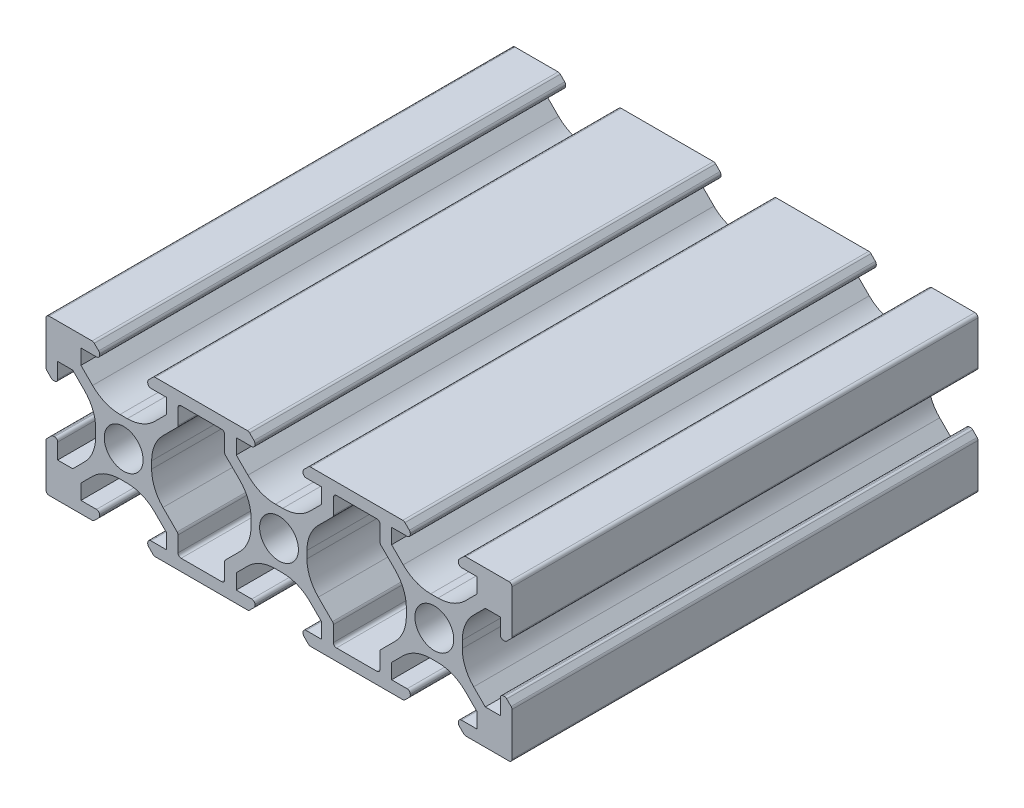
SolidWorks part; units mm, degrees
material "6063-O"
ref_plane "Plano frontal" through (0, 0, 0) normal (0, 0, 1) x (1, 0, 0)
ref_plane "Plano superior" through (0, 0, 0) normal (0, 1, 0) x (1, 0, 0)
ref_plane "Plano direito" through (0, 0, 0) normal (1, 0, 0) x (0, 0, -1)
sketch "Esboço1" plane through (0, 0, 0) normal (0, 0, 1) x (1, 0, 0)
  line L0 (-9.0343, 3.1) -> (-8.9, 3.1)
  line L3 (-10, 10) -> (-4.0657, 10)
  line L5 (-10, -10) -> (10, 10) construction
  line L6 (-10, 10) -> (10, -10) construction
  line L7 (-8.5, 3.5) -> (-8.5, 5.5)
  line L8 (-10, 0) -> (10, 0) construction
  line L9 (0, 10) -> (0, -10) construction
  line L12 (-8.5, 5.5) -> (-6.5607, 5.5)
  line L15 (-6.5607, 5.5) -> (-5.0645, 4.0038)
  line L16 (-3.6, 0.4683) -> (-3.6, 0)
  line L17 (-0.4683, 3.6) -> (0, 3.6)
  line L18 (-5.5, 6.5607) -> (-4.0038, 5.0645)
  line L21 (-5.5, 8.5) -> (-5.5, 6.5607)
  line L24 (-3.5, 8.5) -> (-5.5, 8.5)
  line L25 (-3.1, 9.0343) -> (-3.1, 8.9)
  line L44 (-10, 4.0657) -> (-10, 10)
  line L45 (-9.8828, 3.7828) -> (-9.3172, 3.2172)
  line L46 (-3.7828, 9.8828) -> (-3.2172, 9.3172)
  line L47 (-3.6, 0) -> (-2.5, 0)
  line L48 (0, 3.6) -> (0, 2.5)
  arc A0 (-3.5, 8.5) -> (-3.1, 8.9) centre (-3.5, 8.9) ccw
  arc A1 (-3.7828, 9.8828) -> (-4.0657, 10) centre (-4.0657, 9.6) ccw
  arc A2 (-10, 4.0657) -> (-9.8828, 3.7828) centre (-9.6, 4.0657) ccw
  arc A3 (-8.5, 3.5) -> (-8.9, 3.1) centre (-8.9, 3.5) cw
  arc A4 (-3.2172, 9.3172) -> (-3.1, 9.0343) centre (-3.5, 9.0343) cw
  arc A5 (-9.3172, 3.2172) -> (-9.0343, 3.1) centre (-9.0343, 3.5) ccw
  arc A6 (-3.6, 0.4683) -> (-5.0645, 4.0038) centre (-8.6, 0.4683) ccw
  arc A7 (-4.0038, 5.0645) -> (-0.4683, 3.6) centre (-0.4683, 8.6) ccw
  circle A8 centre (0, 0) radius 2.5
  point P6 (-10, 3.1)
  point P28 (-3.1, 8.5)
  point P31 (-3.1, 10)
  point P33 (-3.9, 10)
  point P36 (-10, 3.9)
  point P39 (-8.5, 3.1)
  point P42 (-3.1, 9.2)
  point P45 (-9.2, 3.1)
  point P48 (-3.6, 2.5393)
  point P51 (-2.5393, 3.6)
  dimension "D5" = 10
  dimension "D9" = 0.4
  dimension "D10" = 0.4
  dimension "D11" = 5
  dimension "D12" = 5
  dimension "D13" = 5
  dimension "D1" = 6.9
  dimension "D2" = 1.5
  dimension "D3" = 3.6
  dimension "D4" = 1.5
  dimension "D6" = 2.4
  dimension "D7" = 3.6
  dimension "D8" = 45
extrude "Ressalto-extrusão1" add sketch "Esboço1" along normal blind 60
sketch "Esboço3" plane through (0, 0, 0) normal (1, 0, 0) x (0, 0, -1)
  line L0 (0, 0) -> (-1000, 0) construction
  dimension "D1" = 1000
pattern_circular "PadrãoCircular1" count 4 over 360 about axis through (0, 0, 0) along (0, 0, 1) of "Ressalto-extrusão1"
pattern_linear "Padrão linear1" count 3 spacing 20 along (1, 0, 0) of "Ressalto-extrusão1", "PadrãoCircular1"
sketch "Esboço4" plane through (0, 0, 0) normal (0, 0, -1) x (-1, 0, 0)
  line L0 (-13.4393, 5.5) -> (-13, 5.9393)
  line L1 (-13, 8.5) -> (-13, 5.9393)
  line L2 (-10, 10) -> (-10, -10) construction
  line L3 (-4.0657, 10) -> (-15.9343, 10) construction
  line L4 (-15.9343, -10) -> (-4.0657, -10) construction
  line L5 (-11.5, 5.5) -> (-13.4393, 5.5) construction
  line L6 (-14.5, 8.5) -> (-14.5, 6.5607) construction
  line L7 (-7, 8.5) -> (-7, 5.9393)
  line L8 (-6.5607, 5.5) -> (-7, 5.9393)
  line L9 (-13, 8.5) -> (-7, 8.5)
  line L10 (-20, 0) -> (0, 0) construction
  line L11 (-13, -8.5) -> (-7, -8.5)
  line L12 (-6.5607, -5.5) -> (-7, -5.9393)
  line L13 (-7, -8.5) -> (-7, -5.9393)
  line L14 (-13, -8.5) -> (-13, -5.9393)
  line L15 (-13.4393, -5.5) -> (-13, -5.9393)
  line L16 (-13.4393, 5.5) -> (-13.4393, -5.5)
  line L17 (-6.5607, -5.5) -> (-6.5607, 5.5)
  line L31 (-40, 0) -> (-20, 0) construction
  line L32 (-33.4393, 5.5) -> (-33, 5.9393) [skipped]
  line L33 (-33, 8.5) -> (-33, 5.9393) [skipped]
  line L34 (-27, 8.5) -> (-27, 5.9393) [skipped]
  line L35 (-26.5607, 5.5) -> (-27, 5.9393) [skipped]
  line L36 (-33, 8.5) -> (-27, 8.5) [skipped]
  line L37 (-33, -8.5) -> (-27, -8.5) [skipped]
  line L38 (-26.5607, -5.5) -> (-27, -5.9393) [skipped]
  line L39 (-27, -8.5) -> (-27, -5.9393) [skipped]
  line L40 (-33, -8.5) -> (-33, -5.9393) [skipped]
  line L41 (-33.4393, -5.5) -> (-33, -5.9393) [skipped]
  line L42 (-33.4393, 5.5) -> (-33.4393, -5.5) [skipped]
  line L43 (-26.5607, -5.5) -> (-26.5607, 5.5) [skipped]
  line L44 (-30, 10) -> (-30, -10) construction
  dimension "D1" = 45
  dimension "D2" = 1.5
  dimension "D3" = 1.5
  dimension "D4" = 2
extrude "Corte-extrusão1" cut sketch "Esboço4" against normal through all
pattern_linear "Padrão linear2" count 2 spacing 20 along (1, 0, 0) of "Corte-extrusão1"
fillet "Filete1" radius 0.4 16 edges at (13, -5.9393, 30) (13, -8.5, 30) (7, -8.5, 30) (7, -5.9393, 30) (7, 8.5, 30) (7, 5.9393, 30) (13, 8.5, 30) (13, 5.9393, 30) (27, -8.5, 30) (27, -5.9393, 30) (27, 8.5, 30) (27, 5.9393, 30) (33, 8.5, 30) (33, -8.5, 30) (33, -5.9393, 30) (33, 5.9393, 30)
fillet "Filete2" radius 0.4 4 edges at (-10, 10, 30) (50, -10, 30) (50, 10, 30) (-10, -10, 30)
ref_plane "Plane1" through (0, 0, 0) normal (0, 1, 0) x (1, 0, 0)
ref_plane "Plane2" through (20, 0, 0) normal (1, 0, 0) x (0, 0, -1)
ref_plane "Plane3" through (0, 0, 30) normal (0, 0, -1) x (-1, 0, 0)
